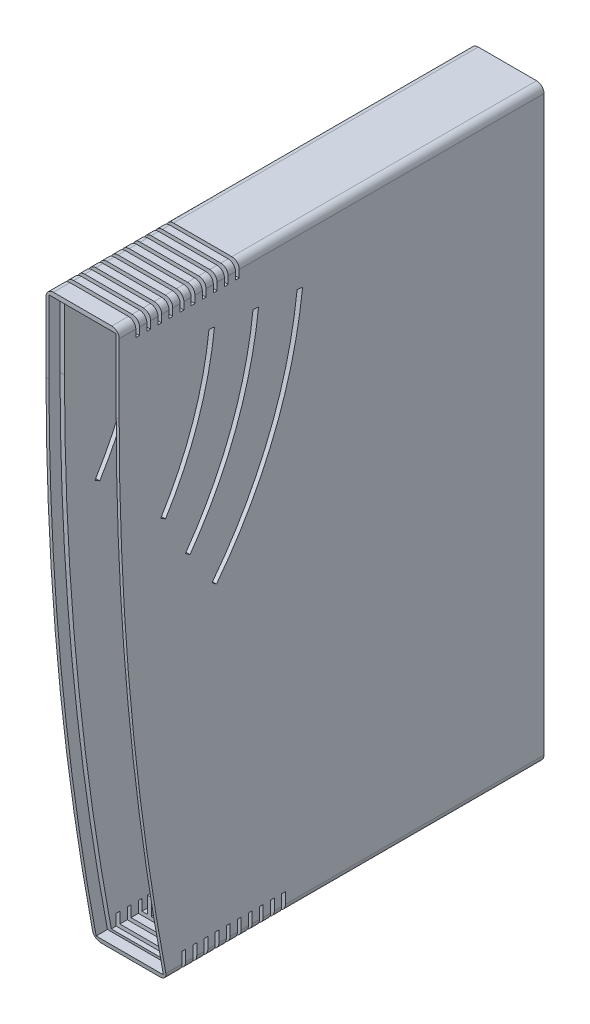
SolidWorks part; units mm, degrees
ref_plane "Front Plane" through (0, 0, 0) normal (0, 0, 1) x (1, 0, 0)
ref_plane "Top Plane" through (0, 0, 0) normal (0, 1, 0) x (1, 0, 0)
ref_plane "Right Plane" through (0, 0, 0) normal (1, 0, 0) x (0, 0, -1)
sketch "Sketch1" plane through (0, 0, 0) normal (0, 0, 1) x (1, 0, 0)
  line L1 (-9.905, -79.55) -> (9.905, -79.55)
  line L2 (-9.905, -79.55) -> (-9.905, 79.55)
  line L3 (-9.905, 79.55) -> (9.905, 79.55)
  line L4 (9.905, -79.55) -> (9.905, 79.55)
  line L5 (-9.905, -79.55) -> (9.905, 79.55) construction
  line L6 (-9.905, 79.55) -> (9.905, -79.55) construction
  point P0 (0, 0)
  dimension "D1" = 19.81
  dimension "D2" = 159.1
extrude "Boss-Extrude1" add sketch "Sketch1" along normal blind 115
shell "Shell1" thickness 2
sketch "Sketch2" plane through (9.905, 0, 0) normal (1, 0, 0) x (0, 0, -1)
  line L2 (-115, 79.55) -> (-115, 58.65)
  line L3 (-115, -79.55) -> (-115, 79.55) construction
  line L4 (-115, -79.55) -> (0, -79.55) construction
  arc A0 (-115, 58.65) -> (-102, -79.55) centre (626.0862, 58.65) ccw
  dimension "D1" = 20.9
  dimension "D2" = 13
extrude "Cut-Extrude1" cut sketch "Sketch2" along normal through all and the other way through all flip side to cut
fillet "Fillet1" radius 2 4 edges at (-9.905, -79.55, 51) (9.905, -79.55, 51) (-9.905, 79.55, 57.5) (9.905, 79.55, 57.5)
sketch "Sketch3" plane through (0, 79.55, 0) normal (0, 1, 0) x (1, 0, 0)
  line L0 (7.905, -115) -> (-7.905, -115) construction
  line L1 (-10.5, -109.5) -> (10.5, -109.5)
  line L2 (-10.5, -109.5) -> (-10.5, -110.5)
  line L3 (-10.5, -110.5) -> (10.5, -110.5)
  line L4 (10.5, -109.5) -> (10.5, -110.5)
  line L5 (-10.5, -109.5) -> (10.5, -110.5) construction
  line L6 (-10.5, -110.5) -> (10.5, -109.5) construction
  line L7 (0, -115) -> (0, -105.7345) construction
  point P0 (0, -110)
  dimension "D1" = 1
  dimension "D2" = 5
  dimension "D3" = 21
extrude "Cut-Extrude2" cut sketch "Sketch3" against normal blind 4
pattern_linear "LPattern1" count 10 spacing 3 along (0, 0, -1) of "Cut-Extrude2"
sketch "Sketch8" plane through (0, -79.55, 0) normal (0, -1, 0) x (1, 0, 0)
  line L0 (-7.905, 102) -> (7.905, 102) construction
  line L1 (-13.3258, 98) -> (14.3742, 98)
  line L2 (-13.3258, 98) -> (-13.3258, 97)
  line L3 (-13.3258, 97) -> (14.3742, 97)
  line L4 (14.3742, 98) -> (14.3742, 97)
  dimension "D1" = 4
  dimension "D2" = 1
extrude "Cut-Extrude4" cut sketch "Sketch8" against normal blind 5
pattern_linear "LPattern2" count 10 spacing 3 along (0, 0, -1) of "Cut-Extrude4"
sketch "Sketch5" plane through (-9.905, 0, 0) normal (-1, 0, 0) x (0, 0, 1)
  line L0 (65.347, 64.8235) -> (66.8382, 64.9865)
  line L1 (77.276, 66.1274) -> (78.7671, 66.2904)
  line L2 (89.2049, 67.4313) -> (90.6961, 67.5942)
  line L3 (88.6672, 6.884) -> (89.8554, 7.7995)
  line L5 (95.8273, 17.3757) -> (97.0496, 18.2452)
  line L6 (102.4576, 29.0608) -> (103.7315, 29.8528)
  arc A0 (90.6961, 67.5942) -> (103.7315, 29.8528) centre (180.1632, 77.3732) ccw
  arc A1 (89.2049, 67.4313) -> (102.4576, 29.0608) centre (180.1632, 77.3732) ccw
  arc A2 (77.276, 66.1274) -> (95.8273, 17.3757) centre (180.1632, 77.3732) ccw
  arc A3 (78.7671, 66.2904) -> (97.0496, 18.2452) centre (180.1632, 77.3732) ccw
  arc A4 (66.8382, 64.9865) -> (89.8554, 7.7995) centre (180.1632, 77.3732) ccw
  arc A5 (65.347, 64.8235) -> (88.6672, 6.884) centre (180.1632, 77.3732) ccw
  arc A6 (90.6961, 67.5942) -> (108.8676, 22.4466) centre (180.1632, 77.3732) ccw construction
  arc A7 (89.2049, 67.4313) -> (107.6794, 21.5311) centre (180.1632, 77.3732) ccw construction
  arc A8 (78.7671, 66.2904) -> (99.3615, 15.123) centre (180.1632, 77.3732) ccw construction
  arc A9 (77.276, 66.1274) -> (98.1733, 14.2076) centre (180.1632, 77.3732) ccw construction
  dimension "D6" = 90
  dimension "D4" = 12
  dimension "D1" = 1.5
  dimension "D2" = 12
  dimension "D3" = 1.5
  dimension "D5" = 1.5
extrude "Cut-Extrude3" cut sketch "Sketch5" against normal through all
ref_plane "Plane1" through (0, 0, 95) normal (0, 0, 1) x (1, 0, 0)
sketch "Sketch7" plane through (0, 0, 95) normal (0, 0, 1) x (1, 0, 0)
  line L0 (-6.405, 77.55) -> (-6.405, 73.05)
  line L1 (-6.405, 73.05) -> (-5.405, 73.05)
  line L2 (-5.405, 73.05) -> (-5.405, 77.55)
  line L3 (-5.405, 77.55) -> (-6.405, 77.55)
  line L4 (-3.605, 77.55) -> (-3.605, 73.05)
  line L5 (7.905, 77.55) -> (-7.905, 77.55) construction
  line L6 (-3.605, 73.05) -> (-2.605, 73.05)
  line L7 (-2.605, 73.05) -> (-2.605, 77.55)
  line L8 (-2.605, 77.55) -> (-3.605, 77.55)
  line L9 (-7.905, 77.55) -> (-7.905, -77.55) construction
  dimension "D1" = 2.5
  dimension "D2" = 1
  dimension "D3" = 1.8
  dimension "D4" = 4.5
  dimension "D5" = 1
extrude "Boss-Extrude3" add sketch "Sketch7" against normal blind 90
chamfer "Chamfer2" distance 0.5 angle 45 2 edges at (-3.605, 75.3, 95) (-5.405, 75.3, 95)
sketch "Sketch10" plane through (0, 0, 0) normal (1, 0, 0) x (0, 0, -1)
  line L1 (-131.7092, 78.35) -> (-112, 78.35)
  line L2 (-112, 58.65) -> (-112, 77.55)
  line L3 (-112, 58.65) -> (-112, 78.35)
  line L4 (-110.5, 77.55) -> (-115, 77.55) construction
  line L5 (-102.9238, -78.35) -> (-99.1739, -78.35)
  line L6 (-102.3768, -77.55) -> (-98, -77.55) construction
  line L7 (-131.7092, 78.35) -> (-102.9238, -78.35)
  arc A3 (-112, 58.65) -> (-99.4279, -76.9986) centre (626.0862, 58.65) ccw
  arc A4 (-112, 58.65) -> (-99.1739, -78.35) centre (626.0862, 58.65) ccw
  dimension "D2" = 0.8
  dimension "D3" = 0.8
  dimension "D1" = 3
extrude "Cut-Extrude6" cut sketch "Sketch10" against normal mid plane 18.21
sketch "Sketch11" plane through (0, 0, 2) normal (0, 0, 1) x (1, 0, 0)
  line L0 (7.905, -77.55) -> (-7.905, -77.55) construction
  line L1 (-6.405, -77.55) -> (-5.405, -77.55)
  line L2 (-6.405, -77.55) -> (-6.405, -73.05)
  line L3 (-6.405, -73.05) -> (-5.405, -73.05)
  line L4 (-5.405, -77.55) -> (-5.405, -73.05)
  line L5 (-7.905, -77.55) -> (7.905, -77.55) construction
  line L6 (-3.605, -77.55) -> (-2.605, -77.55)
  line L7 (-3.605, -77.55) -> (-3.605, -73.05)
  line L8 (-3.605, -73.05) -> (-2.605, -73.05)
  line L9 (-2.605, -77.55) -> (-2.605, -73.05)
  line L10 (-7.905, 77.55) -> (-7.905, -77.55) construction
  dimension "D2" = 4.5
  dimension "D3" = 2.5
  dimension "D4" = 1
  dimension "D5" = 1.8
  dimension "D6" = 1
extrude "Boss-Extrude6" add sketch "Sketch11" along normal blind 89
sketch "Sketch12" plane through (0, 0, 0) normal (0, 0, -1) x (-1, 0, 0)
  line L0 (9.905, 77.55) -> (9.905, -77.55) construction
  line L1 (-8.405, 71.45) -> (7.905, 71.45)
  line L2 (-8.405, 71.45) -> (-8.405, 47.05)
  line L3 (-8.405, 47.05) -> (7.905, 47.05)
  line L4 (7.905, 71.45) -> (7.905, 47.05)
  line L6 (-9.905, 58.65) -> (-9.905, 77.55) construction
  line L7 (-7.905, 79.55) -> (7.905, 79.55) construction
  line L8 (-8.145, 0.15) -> (8.155, 0.15) construction
  line L9 (-8.445, 0.45) -> (8.455, 0.45)
  line L10 (-8.445, 0.45) -> (-8.445, -18.05)
  line L11 (-8.445, -18.05) -> (8.455, -18.05)
  line L12 (8.455, 0.45) -> (8.455, -18.05)
  line L13 (-8.445, -36.87) -> (8.455, -36.87)
  line L14 (-8.445, -36.87) -> (-8.445, -55.37)
  line L15 (-8.445, -55.37) -> (8.455, -55.37)
  line L16 (8.455, -36.87) -> (8.455, -55.37)
  line L17 (-6.945, -60.1813) -> (7.305, -60.1813)
  line L18 (-6.945, -60.1813) -> (-6.945, -71.4313)
  line L19 (-6.945, -71.4313) -> (7.305, -71.4313)
  line L20 (7.305, -60.1813) -> (7.305, -71.4313)
  line L21 (-8.145, -17.75) -> (8.155, -17.75) construction
  line L22 (8.155, -17.05) -> (8.155, -0.55) construction
  line L23 (-8.145, -17.05) -> (-8.145, -0.55) construction
  line L24 (-8.145, -54.37) -> (-8.145, -37.87) construction
  line L25 (8.155, -54.37) -> (8.155, -37.87) construction
  line L26 (-8.145, -37.17) -> (8.155, -37.17) construction
  line L27 (7.005, -71.1313) -> (7.005, -60.4813) construction
  line L28 (3.5828, -60.4813) -> (-6.645, -60.4813) construction
  line L30 (-6.645, -60.4813) -> (-6.645, -71.1313) construction
  line L31 (3.5828, -71.1313) -> (-6.645, -71.1313) construction
  point P8 (-9.905, 68.1)
  dimension "D1" = 2
  dimension "D2" = 1.5
  dimension "D3" = 8.1
  dimension "D4" = 24.4
  dimension "D5" = 0.3
  dimension "D6" = 0.3
  dimension "D7" = 0.3
  dimension "D8" = 0.3
  dimension "D9" = 0.3
  dimension "D10" = 0.3
  dimension "D11" = 0.3
  dimension "D12" = 0.3
  dimension "D13" = 0.3
  dimension "D14" = 0.3
  dimension "D15" = 0.3
  dimension "D16" = 0.3
extrude "Cut-Extrude7" cut sketch "Sketch12" against normal blind 2
